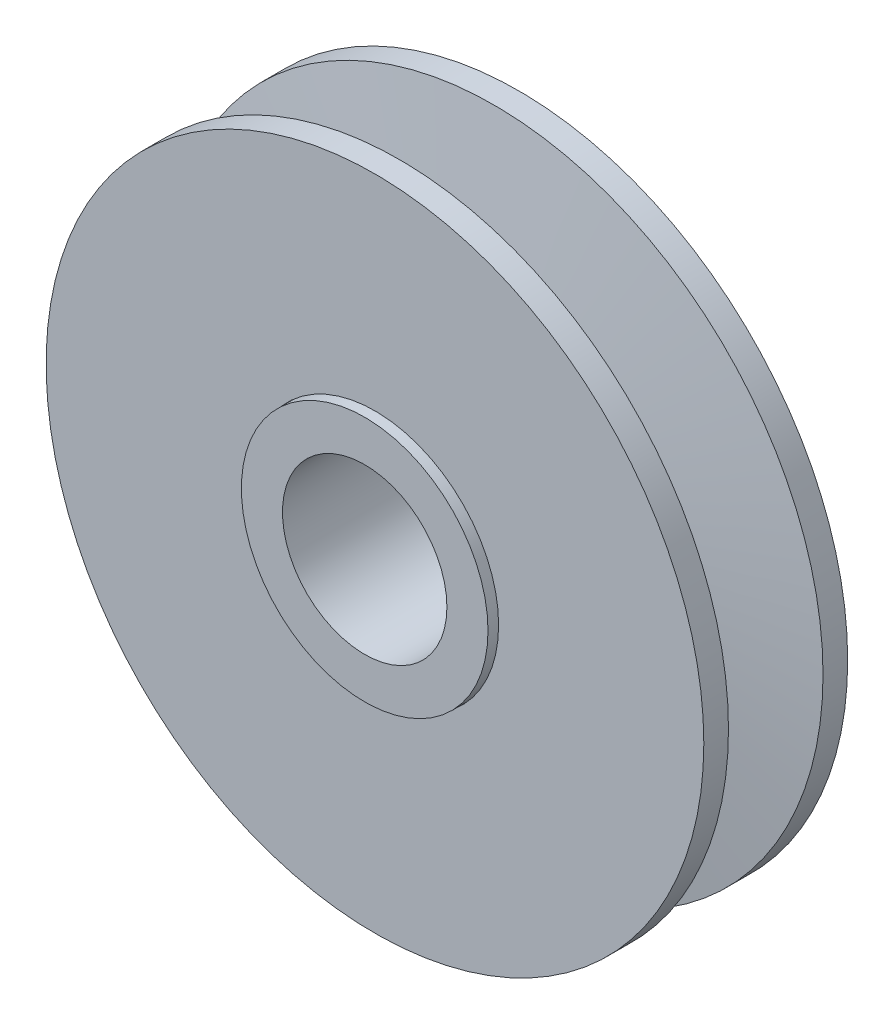
SolidWorks part; units mm, degrees
ref_plane "Front" through (0, 0, 0) normal (0, 0, 1) x (1, 0, 0)
ref_plane "Top" through (0, 0, 0) normal (0, 1, 0) x (1, 0, 0)
ref_plane "Right" through (0, 0, 0) normal (1, 0, 0) x (0, 0, -1)
sketch "Sketch1" plane through (0, 0, 0) normal (1, 0, 0) x (0, 0, -1)
  line L0 (3.6512, 25.4) -> (5.5562, 25.4)
  line L1 (-3.6513, 25.4) -> (-5.5562, 25.4)
  line L2 (-3.6513, 25.4) -> (-2.3639, 14.7943)
  line L4 (6.35, 6.35) -> (-6.35, 6.35)
  line L6 (3.6512, 25.4) -> (2.3639, 14.7943)
  line L8 (-6.35, 0) -> (6.35, 0) construction
  line L9 (-5.5562, 9.525) -> (-5.5562, 25.4)
  line L10 (5.5562, 25.4) -> (5.5563, 9.525)
  line L12 (-5.5562, 9.525) -> (-6.35, 9.525)
  line L13 (-6.35, 9.525) -> (-6.35, 6.35)
  line L14 (0, 12.7) -> (0, -12.7) construction
  line L15 (6.35, 9.525) -> (5.5563, 9.525)
  line L16 (6.35, 9.525) -> (6.35, 6.35)
  line L17 (-5.5562, 25.4) -> (-5.5562, -25.4) construction
  arc A0 (-2.3639, 14.7943) -> (2.3639, 14.7943) centre (0, 15.0813) ccw
  circle A1 centre (0, 15.0813) radius 2.3812 construction
  circle A2 centre (0, 0) radius 6.35 construction
  circle A3 centre (0, 0) radius 9.525 construction
  circle A4 centre (0, 0) radius 15.875 construction
  circle A5 centre (0, -15.0812) radius 2.3812 construction
  point P28 (-5.5562, 0)
  dimension "Rope Dia" = 4.7625
  dimension "D1" = 19.05
  dimension "Shaft Dia" = 12.7
  dimension "D3" = 31.75
  dimension "Wd" = 12.7
  dimension "D8" = 1.905
  dimension "Groove Dia" = 25.4
  dimension "OD" = 50.8
  dimension "w Wd" = 11.1125
revolve "Revolve1" add sketch "Sketch1" angle 360 about L8
sketch "Sketch2" plane through (0, 0, 0) normal (0, 0, 1) x (1, 0, 0)
  circle A0 centre (0, 0) radius 9.525 construction
  circle A1 centre (0, 0) radius 9.525
extrude "Cut-Extrude-Thin1" cut sketch "Sketch2" against normal through all and the other way through all thin
equation "\"D8@Sketch1\" = \"Wd@Sketch1\" * .15"
equation "\"D1@Sketch1\" = \"Shaft Dia@Sketch1\" * 1.5"
equation "\"D3@Sketch1\" = \"Shaft Dia@Sketch1\" * 2.5"
